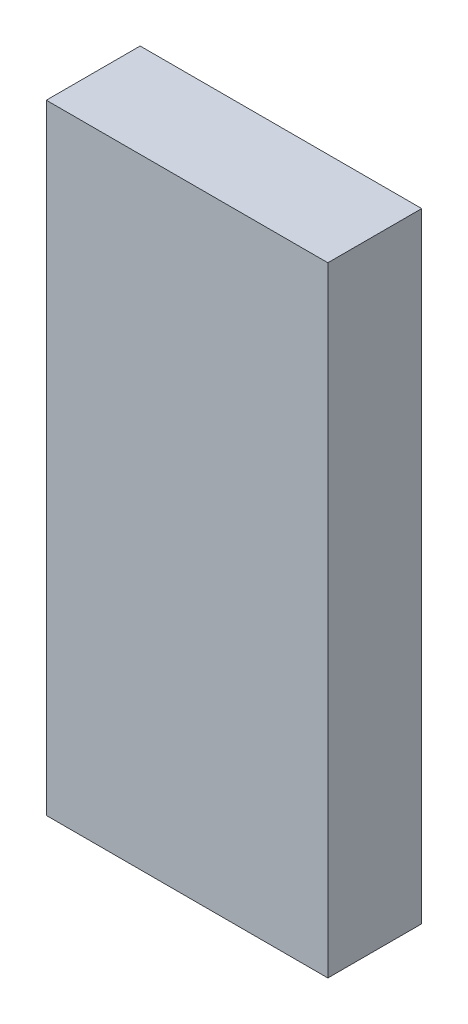
SolidWorks part; units mm, degrees
ref_plane "Front Plane" through (0, 0, 0) normal (0, 0, 1) x (1, 0, 0)
ref_plane "Top Plane" through (0, 0, 0) normal (0, 1, 0) x (1, 0, 0)
ref_plane "Right Plane" through (0, 0, 0) normal (1, 0, 0) x (0, 0, -1)
sketch "Sketch1" plane through (0, 0, 0) normal (0, 0, 1) x (1, 0, 0)
  line L1 (0, 0) -> (15, 0)
  line L2 (0, 0) -> (0, 33)
  line L3 (0, 33) -> (15, 33)
  line L4 (15, 0) -> (15, 33)
  dimension "D1" = 33
  dimension "D2" = 15
extrude "Boss-Extrude1" add sketch "Sketch1" along normal blind 5
